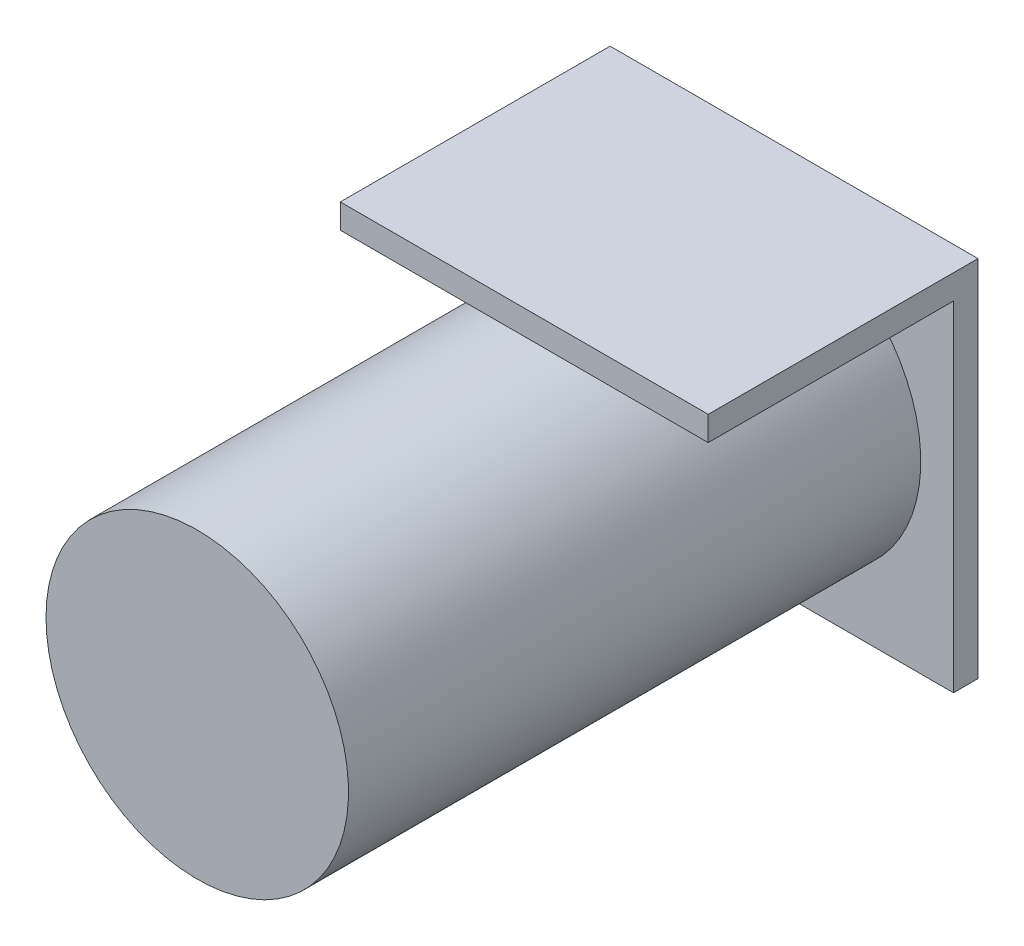
SolidWorks part; units mm, degrees
ref_plane "Front Plane" through (0, 0, 0) normal (0, 0, 1) x (1, 0, 0)
ref_plane "Top Plane" through (0, 0, 0) normal (0, 1, 0) x (1, 0, 0)
ref_plane "Right Plane" through (0, 0, 0) normal (1, 0, 0) x (0, 0, -1)
sketch "SK_Gearmotor" plane through (0, 0, 0) normal (0, 1, 0) x (1, 0, 0)
  line L0 (0, 18) -> (3, 18)
  line L1 (3, 18) -> (3, 0)
  line L2 (3, 0) -> (18.5, 0)
  line L3 (18.5, 0) -> (18.5, -70)
  line L4 (18.5, -70) -> (0, -70)
  line L5 (0, -70) -> (0, 18)
  line L6 (0, 23) -> (0, -75) construction
revolve "Gearmotor" add sketch "SK_Gearmotor" angle 360 about L6
sketch "SK_Bracket_Face" plane through (0, 0, 0) normal (1, 0, 0) x (0, 0, -1)
  line L0 (3, -22.5) -> (0, -22.5)
  line L1 (0, -22.5) -> (0, 22)
  line L2 (0, 22) -> (3, 22)
  line L3 (3, 22) -> (3, -22.5)
extrude "Bracket_Face" add sketch "SK_Bracket_Face" along normal mid plane 45
sketch "SK_Bracket_Top" plane through (0, 0, 0) normal (1, 0, 0) x (0, 0, -1)
  line L0 (3, 19) -> (-30, 19)
  line L1 (-30, 19) -> (-30, 22)
  line L2 (-30, 22) -> (3, 22)
  line L3 (3, 22) -> (3, 19)
extrude "Bracket_Top" add sketch "SK_Bracket_Top" along normal mid plane 45
